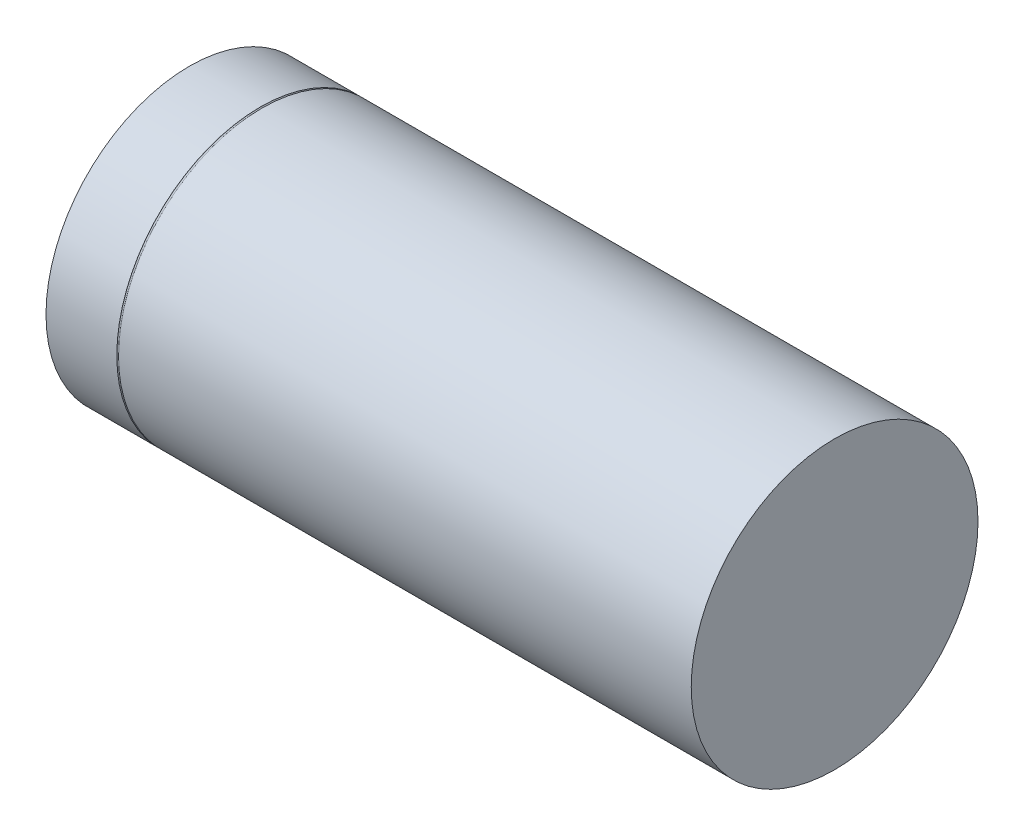
SolidWorks part; units mm, degrees
ref_plane "前视基准面" through (0, 0, 0) normal (0, 0, 1) x (1, 0, 0)
ref_plane "上视基准面" through (0, 0, 0) normal (0, 1, 0) x (1, 0, 0)
ref_plane "右视基准面" through (0, 0, 0) normal (1, 0, 0) x (0, 0, -1)
sketch "Sketch1" plane through (0, 0, 0) normal (1, 0, 0) x (0, 0, -1)
  circle A0 centre (0, 0) radius 16
extrude "Boss-Extrude1" add sketch "Sketch1" along normal blind 72
ref_axis "Axis1" through (72, 0, 0) along (-1, 0, 0)
sketch "Sketch2" plane through (0, 0, 0) normal (0, 0, 1) x (1, 0, 0)
  line L0 (72, 16) -> (0, 16) construction
  line L1 (0, 16) -> (0, -16) construction
  circle A0 centre (8, 16) radius 0.1
  dimension "D1" = 8
revolve "Cut-Revolve1" cut sketch "Sketch2" angle 360 about axis through (72, 0, 0) along (-1, 0, 0)
